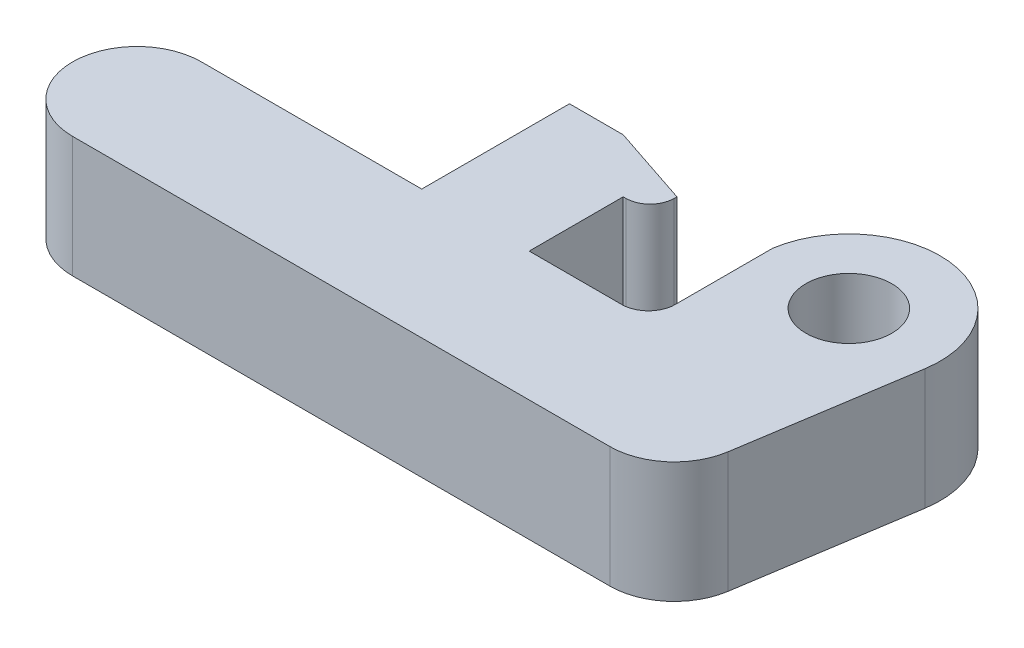
SolidWorks part; units mm, degrees
ref_plane "Front Plane" through (0, 0, 0) normal (0, 0, 1) x (1, 0, 0)
ref_plane "Top Plane" through (0, 0, 0) normal (0, 1, 0) x (1, 0, 0)
ref_plane "Right Plane" through (0, 0, 0) normal (1, 0, 0) x (0, 0, -1)
sketch "Sketch1" plane through (0, 0, 0) normal (0, 1, 0) x (1, 0, 0)
  line L0 (0, 0) -> (0, -6.5) construction
  line L1 (3.3595, -0.5231) -> (2.3714, -6.8692)
  line L2 (-3.3595, 0.5231) -> (-4.0793, -4.1)
  line L3 (0, -6.5) -> (-20, -6.5) construction
  line L4 (0, -8.9) -> (-20, -8.9)
  line L5 (-4.0793, -4.1) -> (-7.8, -4.1)
  line L6 (-7.8, -4.1) -> (-7.8, -0.6)
  line L7 (-7.8, -0.6) -> (-7.7, -0.6)
  line L8 (-9.8, 1.4) -> (-6.8, 0.4)
  line L9 (-9.8, 1.4) -> (-11.8, 1.4)
  line L10 (-11.8, 1.4) -> (-11.8, -4.1)
  line L11 (-6.8, 0.4) -> (-6.8, 0.3)
  line L12 (-11.8, -4.1) -> (-20, -4.1)
  arc A0 (3.3595, -0.5231) -> (-3.3595, 0.5231) centre (0, 0) ccw
  arc A1 (0, -8.9) -> (2.3714, -6.8692) centre (0, -6.5) ccw
  arc A2 (0, -8.9) -> (2.3714, -6.8692) centre (0, -6.5) ccw
  arc A3 (-20, -4.1) -> (-20, -8.9) centre (-20, -6.5) ccw
  circle A4 centre (0, 0) radius 1.6
  arc A5 (-7.7, -0.6) -> (-6.8, 0.3) centre (-7.7, 0.3) ccw
  point P3 (0, 0)
  point P8 (-20, -6.5)
  point P29 (-6.8, -0.6)
  dimension "D2" = 3.2
  dimension "D3" = 3.4
  dimension "D6" = 2.4
  dimension "D13" = 0.9
  dimension "D1" = 4
  dimension "D4" = 20
  dimension "D5" = 6.5
  dimension "D7" = 7.8
  dimension "D8" = 3.5
  dimension "D9" = 1
  dimension "D10" = 2
  dimension "D11" = 1
  dimension "D12" = 3
extrude "Boss-Extrude1" add sketch "Sketch1" along normal blind 4.5 contours L12 A3 L4 A1 L1 A0 L2 L5 L6 L7 L11 L8 L9 L10 A4
sketch "Sketch2" plane through (0, 4.5, 0) normal (0, 1, 0) x (1, 0, 0)
  line L0 (-3.3595, 0.5231) -> (-3.3595, -4.1)
  line L1 (-3.3595, -4.1) -> (-4.0793, -4.1)
  line L2 (-4.0793, -4.1) -> (-3.3595, 0.5231)
extrude "Cut-Extrude1" cut sketch "Sketch2" against normal blind 10
fillet "Fillet1" radius 1 1 edges at (-3.3595, 2.25, 4.1)
